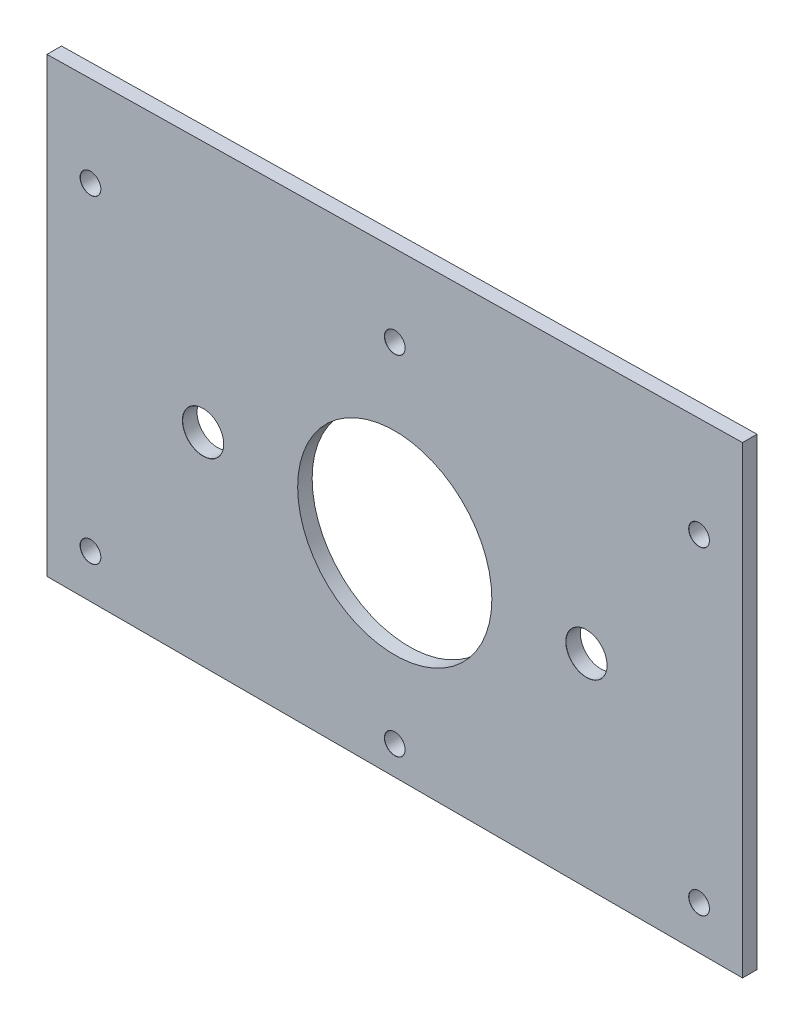
SolidWorks part; units mm, degrees
material "Alloy Steel (SS)"
ref_plane "X-Y Datum" through (0, 0, 0) normal (0, 0, 1) x (1, 0, 0)
ref_plane "X-Z Datum" through (0, 0, 0) normal (0, 1, 0) x (1, 0, 0)
ref_plane "Y-Z Datum" through (0, 0, 0) normal (1, 0, 0) x (0, 0, -1)
sketch "Sketch1" plane through (0, 0, 0) normal (0, 0, 1) x (1, 0, 0)
  line L0 (-76.2, 54.61) -> (-76.2, 44.45)
  line L1 (-76.2, 44.45) -> (76.2, 44.45) construction
  line L2 (-76.2, 44.45) -> (-76.2, -44.45)
  line L3 (-76.2, -44.45) -> (76.2, -44.45)
  line L4 (76.2, 44.45) -> (76.2, -44.45)
  line L5 (-76.2, 44.45) -> (76.2, -44.45) construction
  line L6 (-76.2, -44.45) -> (76.2, 44.45) construction
  line L7 (76.2, 44.45) -> (76.2, 57.15)
  line L10 (-76.2, 54.61) -> (76.2, 57.15)
  point P0 (0, 0)
  dimension "D1" = 152.4
  dimension "D2" = 88.9
  dimension "D3" = 12.7
  dimension "D4" = 10.16
extrude "Boss-Extrude1" add sketch "Sketch1" along normal blind 3.175
hole_wizard "M4 Clearance Hole1" positions "Sketch7" profile "Sketch8" hole size "M4" standard "ANSI Metric" end condition through all
sketch "Sketch7" plane through (0, 0, 3.175) normal (0, 0, 1) x (1, 0, 0)
  line L0 (-75.8701, 0) -> (49924.1299, 0) construction
  line L1 (0, 56.7764) -> (0, -49943.2236) construction
  line L2 (-76.2, -44.45) -> (76.2, -44.45) construction
  line L10 (-76.2, 0) -> (76.2, 0) construction
  line L11 (-76.2, 54.61) -> (-76.2, -44.45) construction
  line L12 (76.2, -44.45) -> (76.2, 57.15) construction
  line L14 (-69.85, -44.45) -> (-69.85, 54.7158) construction
  line L15 (-76.2, -44.45) -> (76.2, -44.45) construction
  line L16 (76.2, 57.15) -> (-76.2, 54.61) construction
  line L17 (69.85, -44.45) -> (69.85, 57.0442) construction
  line L18 (66.675, -44.45) -> (66.675, 56.9912) construction
  line L20 (-66.675, -44.45) -> (-66.675, 54.7687) construction
  line L21 (-76.2, -38.1) -> (76.2, -38.1) construction
  line L22 (-76.2, 34.925) -> (76.2, 34.925) construction
  line L23 (-76.2, -34.925) -> (76.2, -34.925) construction
  line L24 (-76.2, 38.1) -> (76.2, 38.1) construction
  circle A10 centre (-66.675, 34.925) radius 6.35
  circle A11 centre (-66.675, -34.925) radius 6.35
  circle A12 centre (0, -38.1) radius 6.35
  circle A13 centre (66.675, -34.925) radius 6.35
  circle A14 centre (66.675, 34.925) radius 6.35
  circle A15 centre (0, 38.1) radius 6.35
  circle A16 centre (-69.85, 0) radius 6.35
  circle A17 centre (69.85, 0) radius 6.35
  point P174 (-66.675, 34.925)
  point P176 (-66.675, -34.925)
  point P178 (0, -38.1)
  point P180 (66.675, -34.925)
  point P182 (66.675, 34.925)
  point P184 (0, 38.1)
  point P217 (0, 0)
  point P218 (0, 0)
  dimension "D1" = 6.35
  dimension "D9" = 12.7
  dimension "D2" = 146.05
  dimension "D3" = 142.875
  dimension "D4" = 6.35
  dimension "D5" = 9.525
  dimension "D6" = 9.525
  dimension "D7" = 79.375
  dimension "D8" = 82.55
sketch "Sketch8" plane through (0, 38.1, 3.175) normal (1, 0, 0) x (0, -1, 0)
  line L0 (0, 0) -> (0, 3.175)
  line L1 (0, 3.175) -> (2.25, 3.175)
  line L2 (2.25, 3.175) -> (2.25, 0.025)
  line L3 (2.25, 0.025) -> (2.275, 0)
  line L5 (2.275, 0) -> (0, 0)
  line L6 (-2.25, 0.025) -> (-2.275, 0) construction
  line L11 (0, -6.35) -> (0, 107.95) construction
  dimension "Thru Hole Dia." = 4.5
  dimension "Thru Hole Depth" = 3.175
  dimension "Near C'Sink Dia." = 4.55
  dimension "Near C'Sink Angle" = 90
sketch "Sketch9" plane through (0, 0, 3.175) normal (0, 0, 1) x (1, 0, 0)
  line L0 (-42, 0) -> (42, 0) construction
  line L1 (0, -44.45) -> (0, 42.6782) construction
  line L2 (-76.2, -44.45) -> (76.2, -44.45) construction
  circle A0 centre (0, 0) radius 21.275
  circle A1 centre (42, 0) radius 4 construction
  circle A2 centre (-42, 0) radius 4 construction
  dimension "D1" = 42.55
  dimension "D3" = 8
  dimension "D2" = 42
hole_wizard "M8 Clearance Hole1" positions "Sketch10" profile "Sketch11" hole size "M8" standard "ANSI Metric" end condition through all
sketch "Sketch10" plane through (0, 0, 3.175) normal (0, 0, 1) x (1, 0, 0)
  point P0 (-42, 0)
  point P3 (42, 0)
sketch "Sketch11" plane through (-42, 0, 3.175) normal (1, 0, 0) x (0, -1, 0)
  line L0 (0, 0) -> (0, 3.175)
  line L1 (0, 3.175) -> (4.5, 3.175)
  line L2 (4.5, 3.175) -> (4.5, 0.025)
  line L3 (4.5, 0.025) -> (4.525, 0)
  line L5 (4.525, 0) -> (0, 0)
  line L6 (-4.5, 0.025) -> (-4.525, 0) construction
  line L11 (0, -6.35) -> (0, 107.95) construction
  dimension "Thru Hole Dia." = 9
  dimension "Thru Hole Depth" = 3.175
  dimension "Near C'Sink Dia." = 9.05
  dimension "Near C'Sink Angle" = 90
extrude "Center Hole" cut sketch "Sketch9" against normal through all
